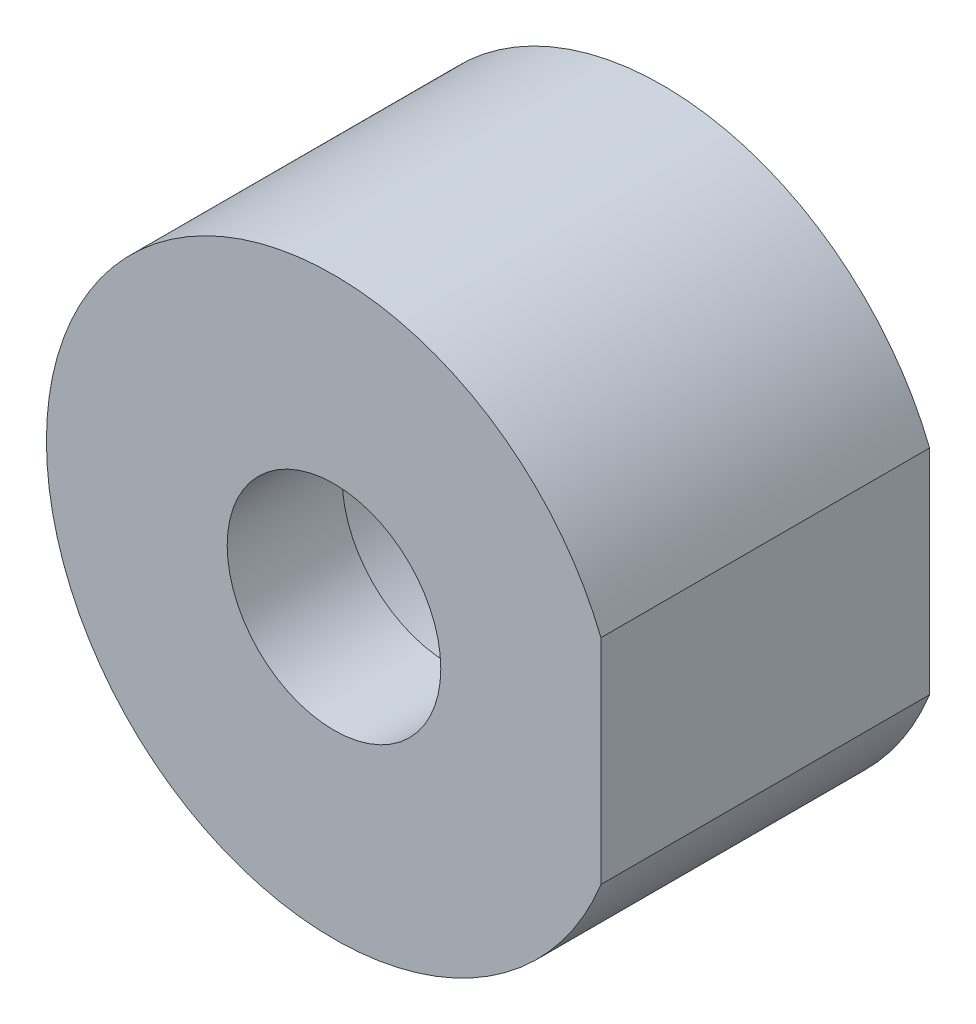
SolidWorks part; units mm, degrees
ref_plane "Спереди" through (0, 0, 0) normal (0, 0, 1) x (1, 0, 0)
ref_plane "Сверху" through (0, 0, 0) normal (0, 1, 0) x (1, 0, 0)
ref_plane "Справа" through (0, 0, 0) normal (1, 0, 0) x (0, 0, -1)
sketch "Эскиз1" plane through (0, 0, 0) normal (0, 0, 1) x (1, 0, 0)
  line L0 (6.4987, -4.835) -> (6.4987, 4.835) construction
  line L1 (6.4987, -2.6014) -> (6.4987, 2.6014)
  circle A0 centre (0, 0) radius 8.1 construction
  arc A1 (6.4987, 2.6014) -> (6.4987, -2.6014) centre (0, 0) ccw
  dimension "D1" = 16.2
  dimension "D3" = 14
  dimension "D2" = 9.67
extrude "Бобышка-Вытянуть1" add sketch "Эскиз1" along normal blind 8
sketch "Эскиз2" plane through (0, 0, 0) normal (0, 0, -1) x (-1, 0, 0)
  circle A0 centre (0, 0) radius 3.95
  dimension "D1" = 7.9
extrude "Вырез-Вытянуть1" cut sketch "Эскиз2" against normal blind 5.2
sketch "Эскиз3" plane through (0, 0, 5.2) normal (0, 0, -1) x (-1, 0, 0)
  circle A0 centre (0, 0) radius 2.6
  dimension "D1" = 5.2
extrude "Вырез-Вытянуть2" cut sketch "Эскиз3" against normal blind 5.2
